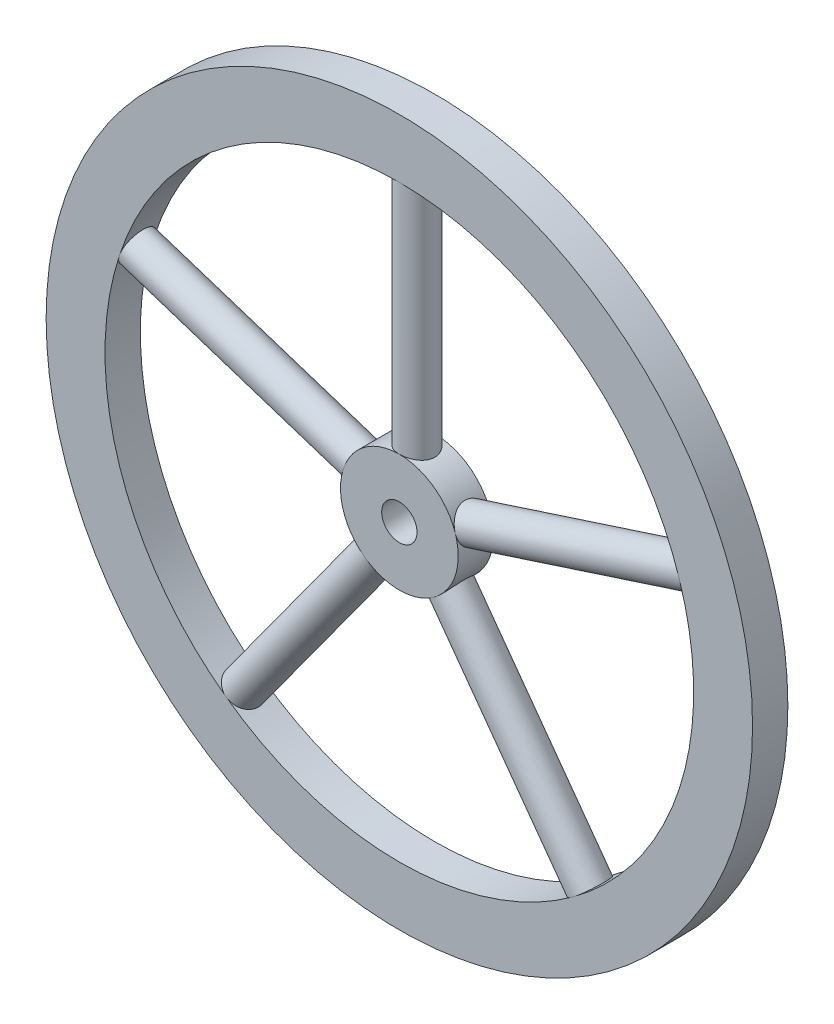
SolidWorks part; units mm, degrees
ref_plane "Front Plane" through (0, 0, 0) normal (0, 0, 1) x (1, 0, 0)
ref_plane "Top Plane" through (0, 0, 0) normal (0, 1, 0) x (1, 0, 0)
ref_plane "Right Plane" through (0, 0, 0) normal (1, 0, 0) x (0, 0, -1)
sketch "Sketch1" plane through (0, 0, 0) normal (0, 0, 1) x (1, 0, 0)
  circle A0 centre (0, 0) radius 15
  circle A1 centre (0, 0) radius 50
  circle A2 centre (0, 0) radius 250
  circle A3 centre (0, 0) radius 300
  dimension "D1" = 600
  dimension "D2" = 500
  dimension "D3" = 100
  dimension "D4" = 30
extrude "Boss-Extrude1" add sketch "Sketch1" along normal mid plane 30 contours A3 A2 | A1 A0
sketch "Sketch2" plane through (0, 0, 0) normal (0, 0, 1) x (1, 0, 0)
  line L0 (0, 0) -> (0, 300) construction
  line L6 (0, 15) -> (15, 15)
  line L10 (0, 265.2516) -> (15, 265.2516)
  line L11 (0, 265.2516) -> (0, 36.4132)
  line L12 (0, 36.4132) -> (15, 36.4132)
  line L13 (15, 265.2516) -> (15, 36.4132)
  circle A1 centre (0, 0) radius 300 construction
  circle A2 centre (0, 0) radius 15 construction
  dimension "D1" = 15
revolve "Revolve1" add sketch "Sketch2" angle 360 about L0
pattern_circular "CirPattern1" count 5 over 360 about axis through (0, 0, 15) along (0, 0, -1) of "Revolve1"
